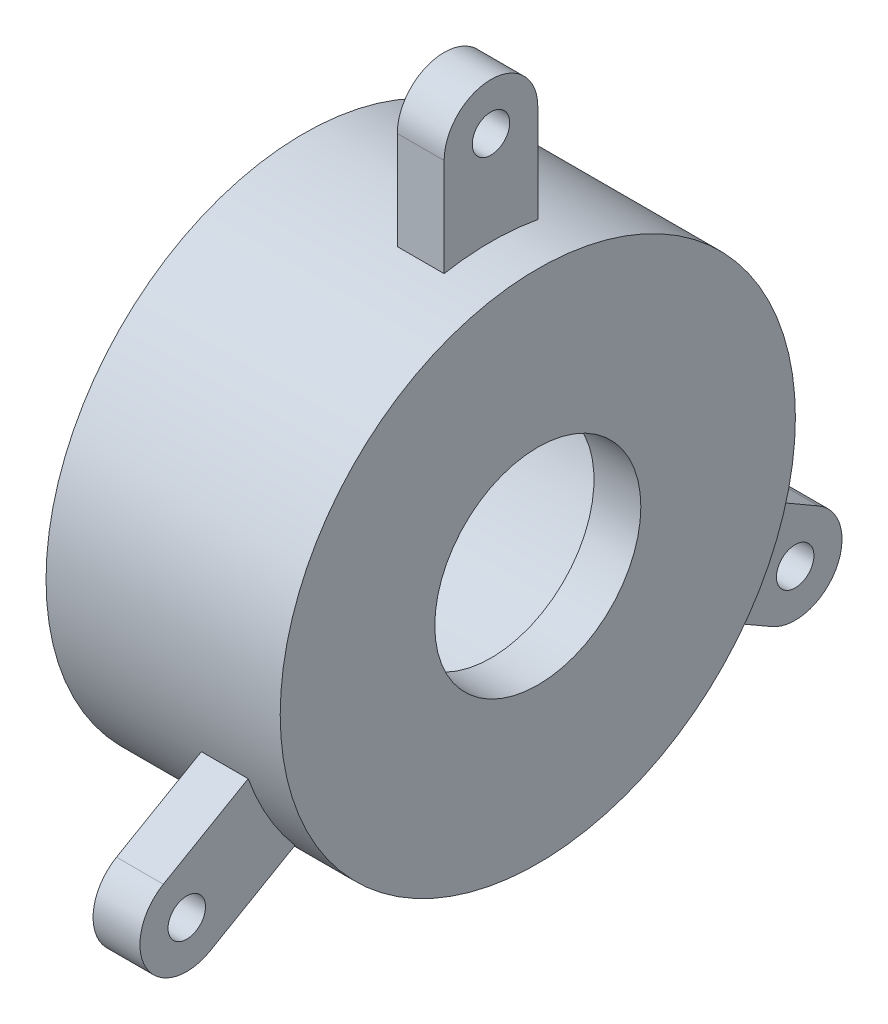
SolidWorks part; units mm, degrees
material "Cast Alloy Steel"
ref_plane "Front Plane" through (0, 0, 0) normal (0, 0, 1) x (1, 0, 0)
ref_plane "Top Plane" through (0, 0, 0) normal (0, 1, 0) x (1, 0, 0)
ref_plane "Right Plane" through (0, 0, 0) normal (1, 0, 0) x (0, 0, -1)
other "Center of Mass"
sketch "Sketch3" plane through (0, 0, 0) normal (0, 0, 1) x (1, 0, 0)
  line L0 (0, 40) -> (0, 55)
  line L1 (0, 55) -> (50, 55)
  line L2 (55, 52) -> (55, 22)
  line L3 (55, 22) -> (40, 22)
  line L4 (0, 40) -> (40, 40)
  line L5 (40, 40) -> (40, 22)
  line L6 (-32.4508, 0) -> (140.7834, 0) construction
  line L7 (50, 55) -> (55, 55)
  line L8 (55, 55) -> (55, 52)
  dimension "D1" = 40
  dimension "D2" = 15
  dimension "D3" = 15
  dimension "D4" = 22
  dimension "D5" = 18
  dimension "D7" = 0
revolve "Revolve1" add sketch "Sketch3" angle 360 about L6
sketch "Sketch4" plane through (55, 0, 0) normal (1, 0, 0) x (0, 0, -1)
  line L0 (0, 51.1006) -> (0, 75) construction
  line L1 (10, 51.1006) -> (10, 75)
  line L2 (-10, 51.1006) -> (-10, 75)
  line L3 (-10, 51.1006) -> (10, 51.1006)
  line L4 (0, 0) -> (0, 75) construction
  line L5 (10, 0) -> (10, 75) construction
  circle A0 centre (0, 75) radius 4
  arc A1 (10, 75) -> (-10, 75) centre (0, 75) ccw
  dimension "D2" = 10
extrude "Boss-Extrude1" add sketch "Sketch4" against normal blind 10 from offset 15 offset against normal yes
pattern_circular "CirPattern1" count 3 over 360 about axis through (0, 0, 0) along (1, 0, 0) of "Boss-Extrude1"
sketch "Sketch7" plane through (55, 0, 0) normal (1, 0, 0) x (0, 0, -1)
  circle A0 centre (0, 0) radius 22
  circle A1 centre (0, 0) radius 55
extrude "Cut-Extrude1" cut sketch "Sketch7" against normal blind 5
